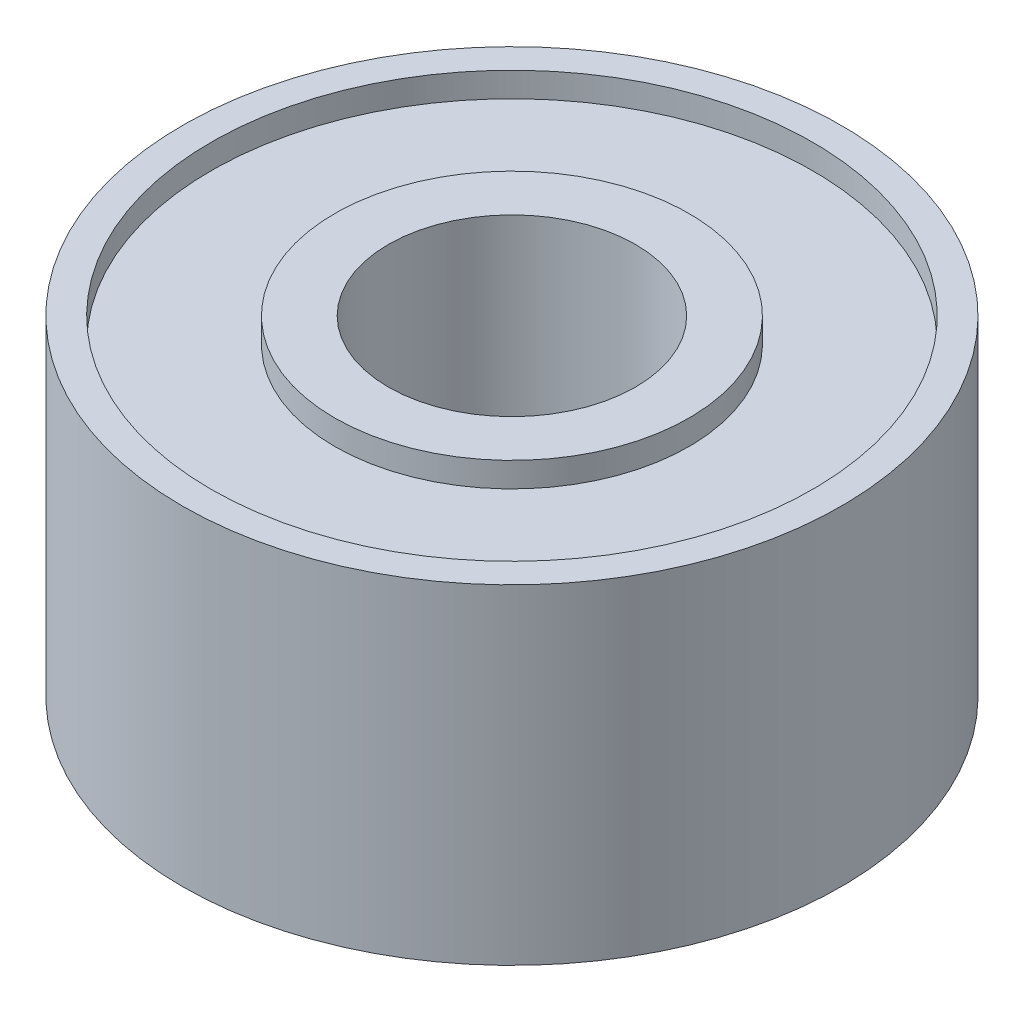
SolidWorks part; units mm, degrees
ref_plane "Front Plane" through (0, 0, 0) normal (0, 0, 1) x (1, 0, 0)
ref_plane "Top Plane" through (0, 0, 0) normal (0, 1, 0) x (1, 0, 0)
ref_plane "Right Plane" through (0, 0, 0) normal (1, 0, 0) x (0, 0, -1)
sketch "Sketch1" plane through (0, 0, 0) normal (0, 1, 0) x (1, 0, 0)
  circle A0 centre (0, 0) radius 4
  circle A1 centre (0, 0) radius 1.5
  dimension "D1" = 8
  dimension "D2" = 3
extrude "Base size" add sketch "Sketch1" along normal blind 4
sketch "Sketch2" plane through (0, 4, 0) normal (0, 1, 0) x (1, 0, 0)
  circle A0 centre (0, 0) radius 1.5 construction
  circle A1 centre (0, 0) radius 4
  circle A2 centre (0, 0) radius 4
  circle A3 centre (0, 0) radius 1.5
  circle A4 centre (0, 0) radius 2.15
  circle A5 centre (0, 0) radius 3.65
  dimension "D2" = 4.3
  dimension "D3" = 0.35
  dimension "D1" = 0
extrude "Bearing features" cut sketch "Sketch2" against normal blind 0.3 contours A5 A4
ref_plane "Center plane" through (0, 2, 0) normal (0, 1, 0) x (1, 0, 0)
mirror "Mirror1" about plane through (0, 2, 0) normal (0, 1, 0) of "Bearing features"
